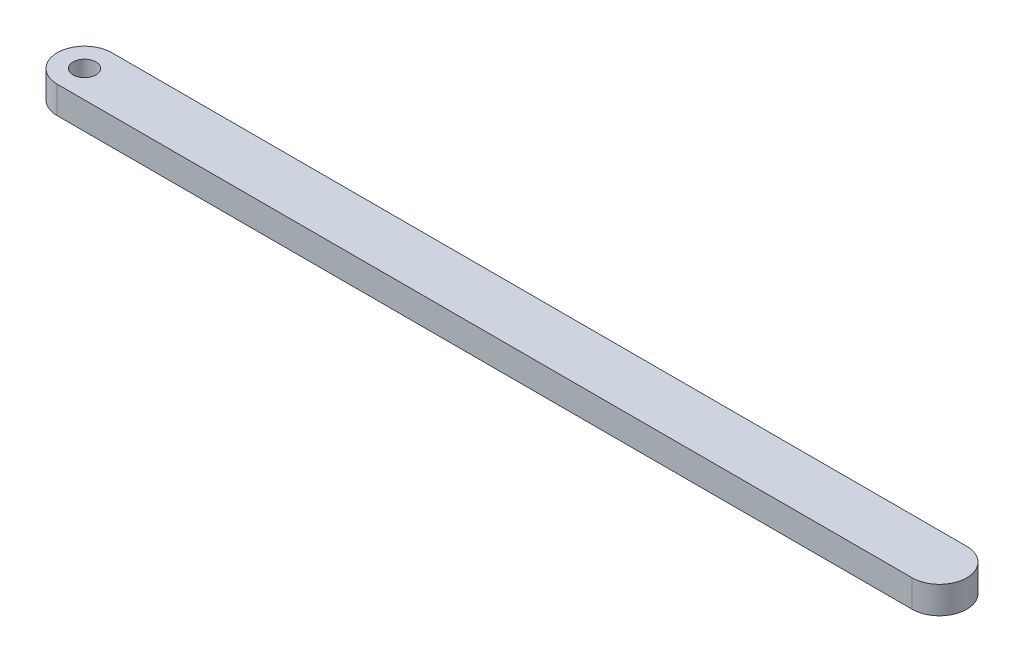
SolidWorks part; units mm, degrees
ref_plane "Front Plane" through (0, 0, 0) normal (0, 0, 1) x (1, 0, 0)
ref_plane "Top Plane" through (0, 0, 0) normal (0, 1, 0) x (1, 0, 0)
ref_plane "Right Plane" through (0, 0, 0) normal (1, 0, 0) x (0, 0, -1)
sketch "Sketch1" plane through (0, 0, 0) normal (0, 1, 0) x (1, 0, 0)
  line L0 (0, 0) -> (188, 0) construction
  line L1 (0, 6) -> (188, 6)
  line L2 (0, -6) -> (188, -6)
  arc A0 (0, 6) -> (0, -6) centre (0, 0) ccw
  arc A1 (188, -6) -> (188, 6) centre (188, 0) ccw
  circle A2 centre (0, 0) radius 2.5
  point P3 (94, 0)
  dimension "D1" = 6
  dimension "D3" = 5
  dimension "D2" = 188
extrude "Boss-Extrude1" add sketch "Sketch1" along normal blind 6
